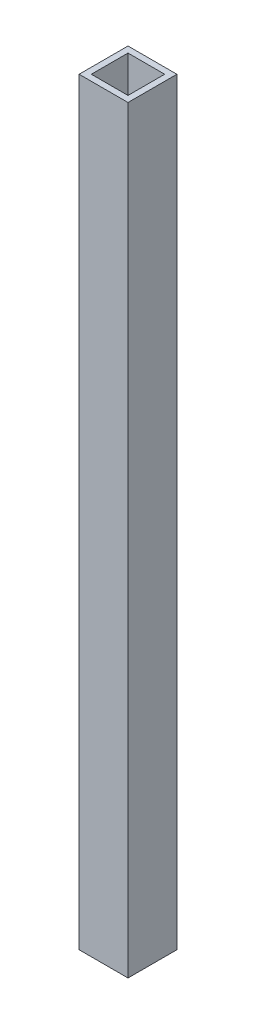
SolidWorks part; units mm, degrees
ref_plane "Front Plane" through (0, 0, 0) normal (0, 0, 1) x (1, 0, 0)
ref_plane "Top Plane" through (0, 0, 0) normal (0, 1, 0) x (1, 0, 0)
ref_plane "Right Plane" through (0, 0, 0) normal (1, 0, 0) x (0, 0, -1)
other "Configuration Table"
sketch "Sketch1" plane through (0, 0, 0) normal (0, 1, 0) x (1, 0, 0)
  line L1 (6.35, 6.35) -> (-6.35, 6.35)
  line L2 (6.35, 6.35) -> (6.35, -6.35)
  line L3 (6.35, -6.35) -> (-6.35, -6.35)
  line L4 (-6.35, 6.35) -> (-6.35, -6.35)
  line L5 (6.35, 6.35) -> (-6.35, -6.35) construction
  line L6 (6.35, -6.35) -> (-6.35, 6.35) construction
  line L7 (4.7625, -4.7625) -> (-4.7625, -4.7625)
  line L8 (4.7625, -4.7625) -> (4.7625, 4.7625)
  line L9 (4.7625, 4.7625) -> (-4.7625, 4.7625)
  line L10 (-4.7625, -4.7625) -> (-4.7625, 4.7625)
  line L11 (4.7625, -4.7625) -> (-4.7625, 4.7625) construction
  line L12 (4.7625, 4.7625) -> (-4.7625, -4.7625) construction
  point P0 (0, 0)
  point P6 (0, 0)
  dimension "D1" = 12.7
  dimension "D2" = 1.5875
extrude "Boss-Extrude1" add sketch "Sketch1" along normal blind 196.85
